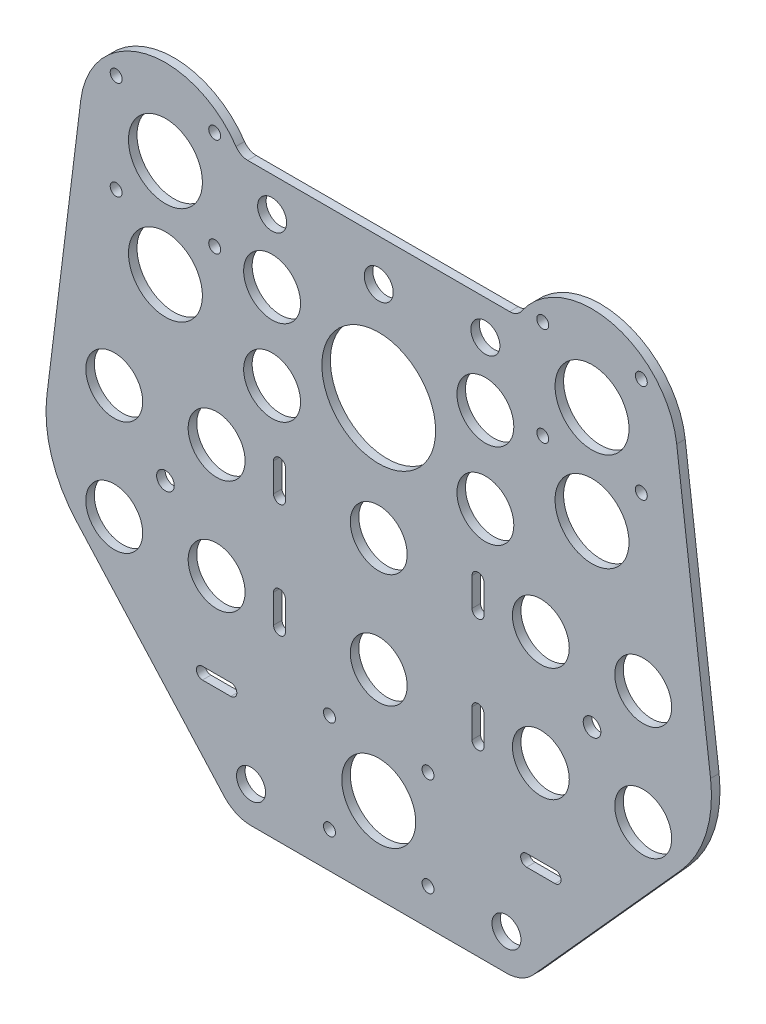
SolidWorks part; units mm, degrees
material "Thornel Mat VMA"
ref_plane "Front Plane" through (0, 0, 0) normal (0, 0, 1) x (1, 0, 0)
ref_plane "Top Plane" through (0, 0, 0) normal (0, 1, 0) x (1, 0, 0)
ref_plane "Right Plane" through (0, 0, 0) normal (1, 0, 0) x (0, 0, -1)
sketch "Model" plane through (0, 0, 0) normal (0, 0, 1) x (1, 0, 0)
  line L0 (-37, 2.8869) -> (-37, -7.1131)
  line L1 (-32.8, 2.8869) -> (-32.8, -7.1131)
  line L2 (-37, -37.1131) -> (-37, -47.1131)
  line L3 (-32.8, -37.1131) -> (-32.8, -47.1131)
  line L4 (-44.9, -112.1131) -> (0, -112.1131)
  line L5 (-46.0542, 89.8869) -> (0, 89.8869)
  line L6 (37, 2.8869) -> (37, -7.1131)
  line L7 (32.8, 2.8869) -> (32.8, -7.1131)
  line L8 (37, -37.1131) -> (37, -47.1131)
  line L9 (32.8, -37.1131) -> (32.8, -47.1131)
  line L10 (44.9, -112.1131) -> (0, -112.1131)
  line L11 (46.0542, 89.8869) -> (0, 89.8869)
  line L12 (-62, -72.1131) -> (-52, -72.1131)
  line L13 (-62, -76.3131) -> (-52, -76.3131)
  line L14 (62, -72.1131) -> (52, -72.1131)
  line L15 (62, -76.3131) -> (52, -76.3131)
  line L16 (-106.2292, -50.1976) -> (-54.3252, -107.9133)
  line L17 (106.2292, -50.1976) -> (54.3252, -107.9133)
  line L18 (-104.7711, 78.91) -> (-116.6795, -16.9345)
  line L19 (104.7711, 78.91) -> (116.6795, -16.9345)
  circle A0 centre (17.3241, -99.4372) radius 2.1
  circle A1 centre (-17.3241, -64.789) radius 2.1
  circle A2 centre (-92.3241, 57.8869) radius 2.1
  circle A3 centre (-57.6759, 92.5351) radius 2.1
  circle A4 centre (0, -82.1131) radius 13
  circle A5 centre (-75, 75.211) radius 13
  circle A6 centre (-92.3241, 92.5351) radius 2.1
  circle A7 centre (-57.6759, 57.8869) radius 2.1
  circle A8 centre (17.3241, -64.789) radius 2.1
  circle A9 centre (-17.3241, -99.4372) radius 2.1
  circle A10 centre (-75, -22.1131) radius 3.1
  circle A11 centre (-57, -2.1131) radius 10
  circle A12 centre (-57, -42.1131) radius 10
  arc A13 (-32.8, 2.8869) -> (-37, 2.8869) centre (-34.9, 2.8869) ccw
  arc A14 (-37, -7.1131) -> (-32.8, -7.1131) centre (-34.9, -7.1131) ccw
  arc A15 (-32.8, -37.1131) -> (-37, -37.1131) centre (-34.9, -37.1131) ccw
  arc A16 (-37, -47.1131) -> (-32.8, -47.1131) centre (-34.9, -47.1131) ccw
  circle A17 centre (-93, -2.1131) radius 10
  circle A18 centre (-93, -42.1131) radius 10
  circle A19 centre (-44.9, -99.4372) radius 5.1
  arc A20 (-50.1893, 92.0761) -> (-104.7711, 78.91) centre (-75, 75.211) ccw
  arc A21 (-50.1893, 92.0761) -> (-46.0542, 89.8869) centre (-46.0542, 94.8869) ccw
  circle A22 centre (75, -22.1131) radius 3.1
  circle A23 centre (57, -2.1131) radius 10
  circle A24 centre (57, -42.1131) radius 10
  arc A25 (37, 2.8869) -> (32.8, 2.8869) centre (34.9, 2.8869) ccw
  arc A26 (32.8, -7.1131) -> (37, -7.1131) centre (34.9, -7.1131) ccw
  arc A27 (37, -37.1131) -> (32.8, -37.1131) centre (34.9, -37.1131) ccw
  arc A28 (32.8, -47.1131) -> (37, -47.1131) centre (34.9, -47.1131) ccw
  circle A29 centre (93, -2.1131) radius 10
  circle A30 centre (93, -42.1131) radius 10
  circle A31 centre (44.9, -99.4372) radius 5.1
  arc A32 (-62, -72.1131) -> (-62, -76.3131) centre (-62, -74.2131) ccw
  arc A33 (-52, -76.3131) -> (-52, -72.1131) centre (-52, -74.2131) ccw
  arc A34 (62, -76.3131) -> (62, -72.1131) centre (62, -74.2131) ccw
  arc A35 (52, -72.1131) -> (52, -76.3131) centre (52, -74.2131) ccw
  circle A36 centre (0, 75.211) radius 5.1
  circle A37 centre (0, -2.1131) radius 10
  circle A38 centre (0, -42.1131) radius 10
  circle A39 centre (0, 40.5628) radius 20
  circle A40 centre (-37.5, 55.5628) radius 10
  circle A41 centre (-37.5, 25.5628) radius 10
  circle A42 centre (37.5, 55.5628) radius 10
  circle A43 centre (37.5, 25.5628) radius 10
  arc A44 (-54.3252, -107.9133) -> (-44.9, -112.1131) centre (-44.9, -99.4372) ccw
  arc A45 (44.9, -112.1131) -> (54.3252, -107.9133) centre (44.9, -99.4372) ccw
  circle A46 centre (57.6759, 57.8869) radius 2.1
  circle A47 centre (92.3241, 92.5351) radius 2.1
  circle A48 centre (75, 75.211) radius 13
  circle A49 centre (57.6759, 92.5351) radius 2.1
  circle A50 centre (92.3241, 57.8869) radius 2.1
  arc A51 (104.7711, 78.91) -> (50.1893, 92.0761) centre (75, 75.211) ccw
  arc A52 (46.0542, 89.8869) -> (50.1893, 92.0761) centre (46.0542, 94.8869) ccw
  arc A53 (-116.6795, -16.9345) -> (-106.2292, -50.1976) centre (-75, -22.1131) ccw
  arc A54 (106.2292, -50.1976) -> (116.6795, -16.9345) centre (75, -22.1131) ccw
  circle A55 centre (-75, 40.6882) radius 13
  circle A56 centre (75, 40.5628) radius 13
  circle A57 centre (-37.5, 77.7248) radius 5.1
  circle A58 centre (37.5, 77.7248) radius 5.1
extrude "Boss-Extrude1" add sketch "Model" along normal blind 3
